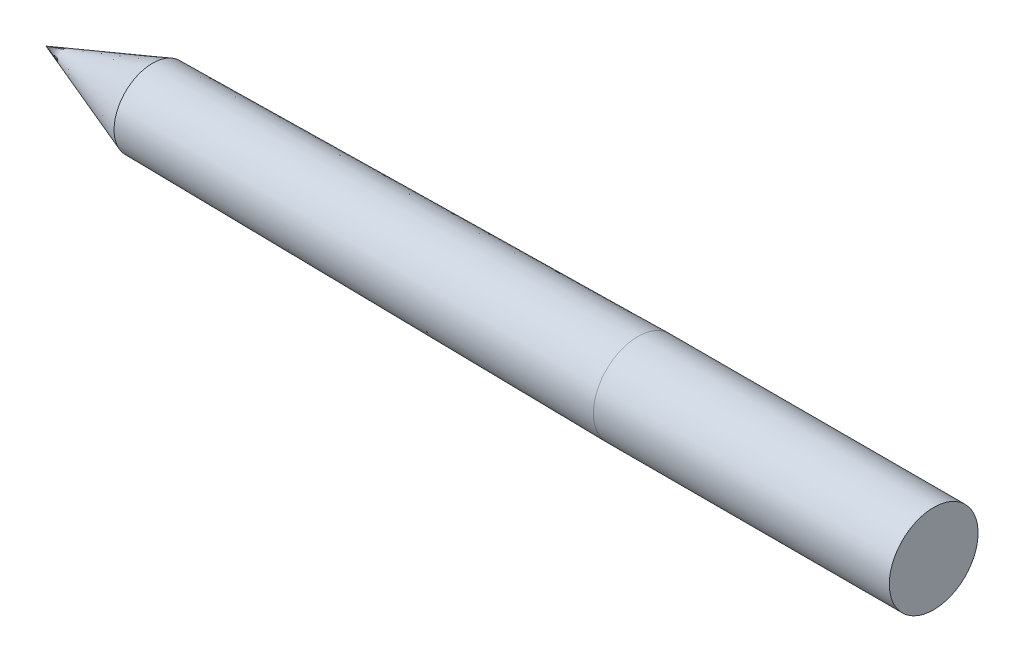
SolidWorks part; units mm, degrees
ref_plane "Front Plane" through (0, 0, 0) normal (0, 0, 1) x (1, 0, 0)
ref_plane "Top Plane" through (0, 0, 0) normal (0, 1, 0) x (1, 0, 0)
ref_plane "Right Plane" through (0, 0, 0) normal (1, 0, 0) x (0, 0, -1)
sketch "Sketch1" plane through (0, 0, 0) normal (0, 0, 1) x (1, 0, 0)
  line L0 (0, 0) -> (20, 0)
  line L2 (3.6, 1.3) -> (0, 0)
  line L3 (3.6, 1.3) -> (20, 1.5)
  line L5 (20, 1.5) -> (30, 1.5)
  line L6 (30, 1.5) -> (30, 0)
  line L7 (30, 0) -> (20, 0)
  dimension "D1" = 1.3
  dimension "D2" = 20
  dimension "D3" = 3.6
  dimension "D4" = 1.5
  dimension "D5" = 1.5
  dimension "D6" = 10
revolve "Revolve1" add sketch "Sketch1" angle 360 about L0
